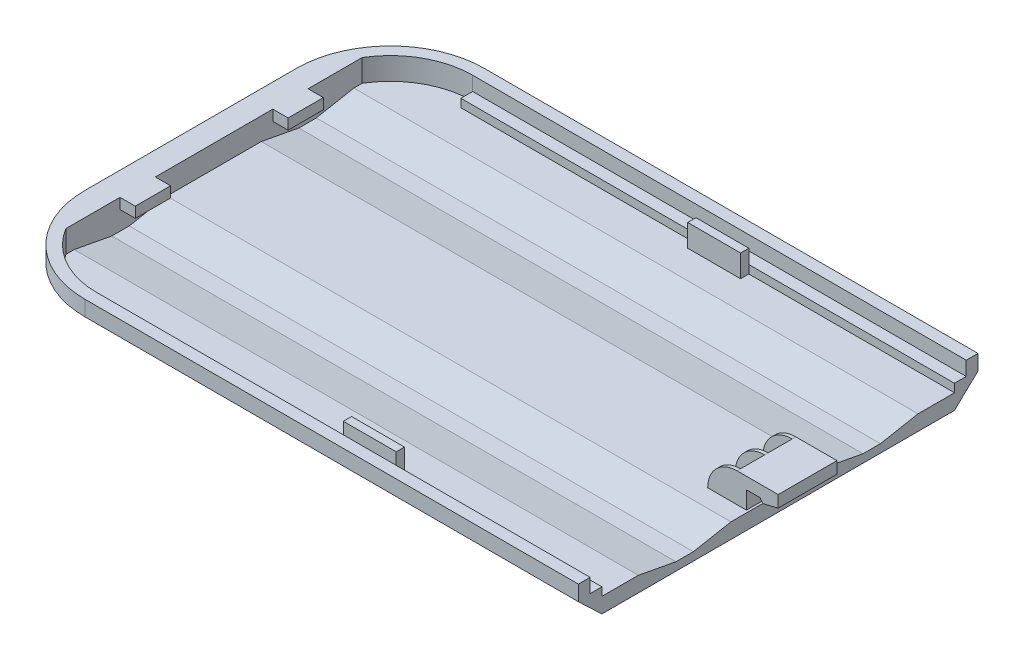
SolidWorks part; units mm, degrees
material "PE High Density"
ref_plane "Front Plane" through (0, 0, 0) normal (0, 0, 1) x (1, 0, 0)
ref_plane "Top Plane" through (0, 0, 0) normal (0, 1, 0) x (1, 0, 0)
ref_plane "Right Plane" through (0, 0, 0) normal (1, 0, 0) x (0, 0, -1)
sketch "Sketch1" plane through (0, 0, 0) normal (1, 0, 0) x (0, 0, -1)
  line L0 (0, 24.9936) -> (0, 1.3) construction
  line L1 (0, 1.76) -> (0, -1.76) construction
  line L3 (-4.0178, 1.3) -> (4.0178, 1.3)
  line L4 (4.0178, 1.3) -> (7.2178, 0.7)
  line L5 (7.2178, 0.7) -> (8.7, 0.7)
  line L6 (8.7, 0.7) -> (11.9, 1.3)
  line L7 (11.9, 1.3) -> (15, 1.3)
  line L8 (15, 1.3) -> (15, 2)
  line L9 (15, 2) -> (16, 2)
  line L10 (16, 2) -> (16, 3.2)
  line L11 (16, 3.2) -> (17, 3.2)
  line L12 (17, 3.2) -> (17, 1.9)
  line L13 (17, 1.9) -> (15, 0)
  line L14 (18.7, 0) -> (-18.7, 0) construction
  line L15 (15, 0) -> (-15, 0)
  line L16 (0, 0) -> (0, -26.6355) construction
  line L17 (-17, 1.9) -> (-15, 0)
  line L18 (-17, 3.2) -> (-17, 1.9)
  line L19 (-16, 3.2) -> (-17, 3.2)
  line L20 (-16, 2) -> (-16, 3.2)
  line L21 (-15, 2) -> (-16, 2)
  line L22 (-15, 1.3) -> (-15, 2)
  line L23 (-11.9, 1.3) -> (-15, 1.3)
  line L24 (-8.7, 0.7) -> (-11.9, 1.3)
  line L25 (-7.2178, 0.7) -> (-8.7, 0.7)
  line L26 (-4.0178, 1.3) -> (-7.2178, 0.7)
  dimension "D1" = 1.3
  dimension "D2" = 1.9
  dimension "D3" = 1
  dimension "D4" = 2
  dimension "D5" = 1
  dimension "D6" = 1.2
  dimension "D7" = 0.7
  dimension "D8" = 3.1
  dimension "D9" = 15
  dimension "D10" = 0.6
  dimension "D11" = 3.2
  dimension "D12" = 0.6
  dimension "D13" = 3.2
extrude "Boss-Extrude1" add sketch "Sketch1" against normal blind 42
sketch "Sketch3" plane through (0, 1.3, 0) normal (0, 1, 0) x (1, 0, 0)
  line L0 (0, 15) -> (-22, 15) construction
  line L1 (-42, 15) -> (0, 15) construction
  line L2 (0, 0) -> (-42, 0) construction
  line L3 (-22, 15) -> (-17.5, 15)
  line L4 (-22, 15) -> (-22, 14.3)
  line L5 (-22, 14.3) -> (-17.5, 14.3)
  line L6 (-17.5, 15) -> (-17.5, 14.3)
  line L7 (-42, 4.0178) -> (-42, -4.0178) construction
  line L8 (-22, -14.3) -> (-17.5, -14.3)
  line L9 (-17.5, -15) -> (-17.5, -14.3)
  line L10 (-22, -15) -> (-17.5, -15)
  line L11 (-22, -15) -> (-22, -14.3)
  dimension "D1" = 22
  dimension "D2" = 4.5
  dimension "D3" = 0.7
extrude "Boss-Extrude2" add sketch "Sketch3" along normal up to vertex (1.9 mm away)
sketch "Sketch5" plane through (0, 0, 0) normal (0, 1, 0) x (1, 0, 0)
  line L0 (0, 0) -> (0, 2.5)
  line L1 (0, 4.0178) -> (0, -4.0178) construction
  line L2 (0, 2.5) -> (-3.5, 2.5)
  line L3 (-3.5, 2.5) -> (-3.5, -2.5)
  line L4 (-3.5, -2.5) -> (0, -2.5)
  line L5 (0, -2.5) -> (0, 0)
  line L6 (0, 0) -> (0, 0.15)
  line L7 (0, 0.15) -> (-3.5, 0.15)
  line L8 (-3.5, 0.15) -> (-3.5, -0.15)
  line L9 (-3.5, -0.15) -> (0, -0.15)
  line L10 (-3.5, 2.2) -> (0, 2.2)
  line L11 (-3.5, -2.2) -> (0, -2.2)
  line L12 (-1, 2.5) -> (-1, -2.5)
  point P18 (0, 1.25)
  dimension "D1" = 2.5
  dimension "D2" = 2.5
  dimension "D3" = 3.5
  dimension "D4" = 1
  dimension "D5" = 0.15
  dimension "D6" = 0.15
  dimension "D7" = 0.3
  dimension "D8" = 0.3
sketch "Sketch6" plane through (0, 1.3, 0) normal (0, 1, 0) x (1, 0, 0)
  line L0 (0, 0) -> (0, 2.5)
  line L1 (0, 2.5) -> (-3.5, 2.5)
  line L2 (-3.5, 2.5) -> (-3.5, -2.5)
  line L3 (-3.5, -2.5) -> (0, -2.5)
  line L4 (0, -2.5) -> (0, 0)
  line L5 (0, 0) -> (0, 0.15)
  line L6 (0, 0.15) -> (-3.5, 0.15)
  line L7 (-3.5, 0.15) -> (-3.5, -0.15)
  line L8 (-3.5, -0.15) -> (0, -0.15)
  line L9 (-3.5, 2.2) -> (0, 2.2)
  line L10 (-3.5, -2.2) -> (0, -2.2)
  line L11 (-1, 2.5) -> (-1, -2.5)
  point P15 (0, 1.25)
  dimension "D1" = 2.5
  dimension "D2" = 2.5
  dimension "D3" = 3.5
  dimension "D4" = 1
  dimension "D5" = 0.15
  dimension "D6" = 0.15
  dimension "D7" = 0.3
  dimension "D8" = 0.3
revolve "Revolve1" add sketch "Sketch6" angle 90 about L11
sketch "Sketch7" plane through (1.6927, 1.3, 1.3259) normal (0, 1, 0) x (1, 0, 0)
  line L0 (-5.1927, -1.1741) -> (0.8073, -1.1741) construction
  line L1 (-1.8927, 3.8259) -> (0.8073, 3.8259)
  line L2 (-1.8927, 3.8259) -> (-1.8927, -1.1741)
  line L3 (-1.8927, -1.1741) -> (0.8073, -1.1741)
  line L4 (0.8073, 3.8259) -> (0.8073, -1.1741)
  dimension "D1" = 2.7
  dimension "D2" = 5
  dimension "D3" = 6
extrude "Boss-Extrude3" add sketch "Sketch7" along normal blind 2.5 separate body contours L2 L1 L4 L3
sketch "Sketch9" plane through (0, 1.3, 0) normal (0, -1, 0) x (1, 0, 0)
  line L1 (-1, 2.5) -> (2.5, 2.5)
  line L2 (-1, 2.5) -> (-1, -2.5)
  line L3 (-1, -2.5) -> (2.5, -2.5)
  line L4 (2.5, 2.5) -> (2.5, -2.5)
extrude "Cut-Extrude1" cut sketch "Sketch9" against normal blind 1.5
sketch "Sketch10" plane through (0, 2.8, 0) normal (0, -1, 0) x (1, 0, 0)
  line L0 (-0.2, -2.5) -> (2.5, -2.5) construction
  line L1 (2.5, 2.5) -> (1, 2.5) construction
  line L2 (2.5, 2.5) -> (2.5, -2.5) construction
  line L3 (2.5, -2.5) -> (1, -2.5) construction
  line L4 (1, 2.5) -> (1, -2.5)
  line L5 (1.3, 2.5) -> (1.3, -2.5) construction
  line L6 (1, 2.5) -> (1.3, 2.5)
  line L7 (1, 2.5) -> (1, -2.5)
  line L8 (1, -2.5) -> (1.3, -2.5)
  line L9 (1.3, 2.5) -> (1.3, -2.5)
  line L10 (1.3, 2.5) -> (1.3, -2.5) construction
  dimension "D1" = 0.3
  dimension "D2" = 1.5
revolve "Revolve2" add sketch "Sketch10" angle 90 about L9
sketch "Sketch11" plane through (0, 0, -2.5) normal (0, 0, -1) x (-1, 0, 0)
  line L0 (-1.3, 2.5) -> (-2.5, 2.8)
  line L1 (-2.5, 2.8) -> (-1.3, 2.8)
  line L2 (-1.3, 2.8) -> (-1.3, 2.5)
extrude "Boss-Extrude5" add sketch "Sketch11" against normal up to vertex
sketch "Sketch20" plane through (-42, 0, 0) normal (-1, 0, 0) x (0, 0, 1)
  line L0 (0, 1.3) -> (0, 0) construction
  line L1 (-0.15, 1.3) -> (0.15, 1.3) construction
  line L2 (17, 3.2) -> (9, 3.2) construction
  line L3 (9, 3.2) -> (9, 0.7562) construction
  line L4 (8.7, 0.7) -> (11.9, 1.3) construction
  line L5 (17, 3.2) -> (17, 1.9)
  line L6 (17, 1.9) -> (15, 0)
  line L7 (18.7, 0) -> (-18.7, 0) construction
  line L8 (17, 1.9) -> (15, 0) construction
  line L9 (15, 0) -> (9, 0)
  line L10 (9, 0) -> (9, 0.7562)
  line L12 (11.9, 1.3) -> (15, 1.3)
  line L13 (17, 3.2) -> (16, 3.2)
  line L14 (16, 3.2) -> (16, 2)
  line L15 (16, 2) -> (16, 1.3)
  line L16 (16, 1.3) -> (15, 1.3)
  line L17 (11.9, 1.3) -> (11.9, 0.7562)
  line L18 (11.9, 0.7562) -> (9, 0.7562)
  dimension "D1" = 8
revolve "Revolve4" add sketch "Sketch20" angle 90 about L10
sketch "Sketch22" plane through (-42, 0, 0) normal (-1, 0, 0) x (0, 0, 1)
  line L0 (-17, 3.2) -> (-9, 3.2) construction
  line L1 (-9, 3.2) -> (-9, 0.7562) construction
  line L2 (-11.9, 1.3) -> (-8.7, 0.7) construction
  line L3 (-9, 0.7562) -> (-9, 0)
  line L4 (18.7, 0) -> (-18.7, 0) construction
  line L5 (-16, 2) -> (-16, 3.2)
  line L6 (-16, 3.2) -> (-17, 3.2)
  line L7 (-17, 3.2) -> (-17, 1.9)
  line L8 (-17, 1.9) -> (-15, 0)
  line L9 (-15, 0) -> (-17, 1.9) construction
  line L10 (-15, 0) -> (-9, 0)
  line L12 (-11.9, 1.3) -> (-15, 1.3)
  line L13 (-15, 1.3) -> (-16, 1.3)
  line L14 (-16, 1.3) -> (-16, 2)
  line L15 (-11.9, 1.3) -> (-11.9, 0.7562)
  line L16 (-11.9, 0.7562) -> (-9, 0.7562)
  dimension "D1" = 8
revolve "Revolve6" add sketch "Sketch22" angle 90 about L1
sketch "Sketch25" plane through (0, 0, -9) normal (0, 0, 1) x (1, 0, 0)
  line L0 (-42, 0) -> (-42, 0.7562)
  line L1 (-42, 0.7562) -> (-44.9, 0.7562)
  line L2 (-44.9, 0.7562) -> (-44.9, 1.3)
  line L3 (-44.9, 1.3) -> (-49, 1.3)
  line L4 (-49, 1.3) -> (-49, 3.2)
  line L5 (-49, 3.2) -> (-50, 3.2)
  line L6 (-50, 3.2) -> (-50, 1.9)
  line L7 (-50, 1.9) -> (-48, 0)
  line L8 (-48, 0) -> (-42, 0)
extrude "Boss-Extrude7" add sketch "Sketch25" along normal up to vertex
sketch "Sketch26" plane through (-42, 0, 0) normal (-1, 0, 0) x (0, 0, 1)
  line L0 (11.9, 0.7562) -> (11.9, 1.3)
  line L1 (11.9, 0.7562) -> (9, 0.7562) construction
  line L2 (11.9, 1.3) -> (11.9, 0.7562) construction
  line L3 (11.9, 1.3) -> (9, 0.7562)
  line L4 (9, 0.7562) -> (11.9, 0.7562)
  line L5 (6.9178, 0.7562) -> (4.0178, 1.3)
  line L6 (4.0178, 1.3) -> (-4.0178, 1.3)
  line L7 (-4.0178, 1.3) -> (-7.0678, 0.7281)
  line L8 (-7.2178, 0.7) -> (-6.9178, 0.7562) construction
  line L9 (-7.0678, 0.7281) -> (6.9178, 0.7562)
  line L10 (-9, 0.7562) -> (-11.9, 1.3)
  line L11 (-11.9, 1.3) -> (-11.9, 0.7562)
  line L12 (-9, 0.7562) -> (-11.9, 0.7562) construction
  line L13 (-11.9, 0.7562) -> (-9, 0.7562)
extrude "Boss-Extrude8" add sketch "Sketch26" along normal up to vertex (2.9 mm away)
sketch "Sketch27" plane through (-42, 0, 0) normal (1, 0, 0) x (0, 0, -1)
  line L0 (-8.7, 0.7) -> (-7.2178, 0.7)
  line L1 (-7.2178, 0.7) -> (-6.9178, 0.7562)
  line L2 (-6.9178, 0.7562) -> (-9, 0.7562)
  line L3 (-9, 0.7562) -> (-8.7, 0.7)
  line L4 (8.7, 0.7) -> (9, 0.7562)
  line L5 (6.9178, 0.7562) -> (9, 0.7562) construction
  line L6 (9, 0.7562) -> (8.7, 0.7) construction
  line L7 (9, 0.7562) -> (6.9178, 0.7562)
  line L8 (6.9178, 0.7562) -> (7.2178, 0.7)
  line L9 (8.7, 0.7) -> (7.2178, 0.7) construction
  line L10 (7.2178, 0.7) -> (8.7, 0.7)
extrude "Cut-Extrude2" cut sketch "Sketch27" against normal up to vertex (2.9 mm away)
sketch "Sketch28" plane through (0, 3.2, 0) normal (0, 1, 0) x (1, 0, 0)
  line L0 (-50, 0) -> (-48, 0) construction
  line L1 (-50, -9) -> (-50, 9) construction
  line L2 (-48, 12.6056) -> (-48, -12.6056)
  line L3 (-48, 12.6056) -> (-49.0521, 11.5535)
  line L4 (-49.0521, 11.5535) -> (-49.5878, 9.6596)
  line L5 (-49.5878, 9.6596) -> (-49.5878, 5.3335)
  line L6 (-49.5878, 5.3335) -> (-49.5878, -9.8966)
  line L7 (-49.5878, -9.8966) -> (-48.526, -12.6056)
  line L8 (-48.526, -12.6056) -> (-48, -12.6056)
  arc A0 (-49, -9) -> (-42, -16) centre (-42, -9) ccw construction
  point P11 (-48, 0)
  dimension "D1" = 2
extrude "Boss-Extrude9" add sketch "Sketch28" against normal up to vertex
sketch "Sketch29" plane through (-48, 0, 0) normal (1, 0, 0) x (0, 0, -1)
  line L0 (0, 3.2) -> (8, 3.2) construction
  line L1 (-12.6056, 3.2) -> (12.6056, 3.2) construction
  line L2 (0, 3.2) -> (0, 1.8211) construction
  line L3 (8, 3.2) -> (5, 3.2)
  line L4 (8, 3.2) -> (8, 2.3)
  line L5 (8, 2.3) -> (5, 2.3)
  line L6 (5, 3.2) -> (5, 2.3)
  line L7 (-8, 2.3) -> (-5, 2.3)
  line L8 (-5, 3.2) -> (-5, 2.3)
  line L9 (-8, 3.2) -> (-5, 3.2)
  line L10 (-8, 3.2) -> (-8, 2.3)
  dimension "D1" = 8
  dimension "D2" = 3
  dimension "D3" = 0.9
extrude "Boss-Extrude10" add sketch "Sketch29" along normal blind 1.3
sketch "Sketch31" plane through (-44.9, 0, 0) normal (1, 0, 0) x (0, 0, -1)
  line L0 (-8.7, 0.7) -> (-7.2178, 0.7)
  line L1 (-7.2178, 0.7) -> (-4.0178, 1.3)
  line L2 (-4.0178, 1.3) -> (-9, 1.3)
  line L3 (-9, 1.3) -> (-11.9, 1.3)
  line L4 (-11.9, 1.3) -> (-8.7, 0.7)
  line L5 (4.0178, 1.3) -> (7.2178, 0.7)
  line L6 (7.2178, 0.7) -> (8.7, 0.7)
  line L7 (8.7, 0.7) -> (11.9, 1.3)
  line L8 (11.9, 1.3) -> (4.0178, 1.3)
extrude "Cut-Extrude3" cut sketch "Sketch31" against normal up to vertex
sketch "Sketch33" plane through (0, 0, 0) normal (1, 0, 0) x (0, 0, -1)
  line L0 (-11.9, 1.3) -> (-4.0178, 1.3)
  line L1 (-4.0178, 1.3) -> (-7.2178, 0.7)
  line L2 (-7.2178, 0.7) -> (-8.7, 0.7)
  line L3 (-8.7, 0.7) -> (-11.9, 1.3)
  line L4 (4.0178, 1.3) -> (11.9, 1.3)
  line L5 (8.7, 0.7) -> (11.9, 1.3) construction
  line L6 (11.9, 1.3) -> (9, 0.7562) construction
  line L7 (11.9, 1.3) -> (8.7, 0.7)
  line L8 (8.7, 0.7) -> (7.2724, 0.7)
  line L9 (7.2178, 0.7) -> (8.7, 0.7) construction
  line L10 (7.2724, 0.7) -> (4.0178, 1.3)
extrude "Cut-Extrude4" cut sketch "Sketch33" against normal up to vertex
sketch "Sketch34" plane through (0, 1.3, 0) normal (0, 1, 0) x (1, 0, 0)
  line L1 (-1, 2.5) -> (-0.2, 2.5)
  line L2 (-1, 2.5) -> (-1, -2.5)
  line L3 (-1, -2.5) -> (-0.2, -2.5)
  line L4 (-0.2, 2.5) -> (-0.2, -2.5)
extrude "Boss-Extrude11" add sketch "Sketch34" along normal up to vertex
sketch "Sketch36" plane through (0, 0, 0) normal (0, 0, 1) x (1, 0, 0)
  line L0 (-50, 1.9) -> (-48, 0)
  line L1 (18.7, 0) -> (-18.7, 0) construction
  line L2 (-48, 0) -> (-49.3684, 1.3) construction
  line L3 (-48, 0) -> (-50, 0)
  line L4 (-50, 0) -> (-50, 1.9)
extrude "Cut-Extrude5" cut sketch "Sketch36" along normal through all and the other way blind 12.7
